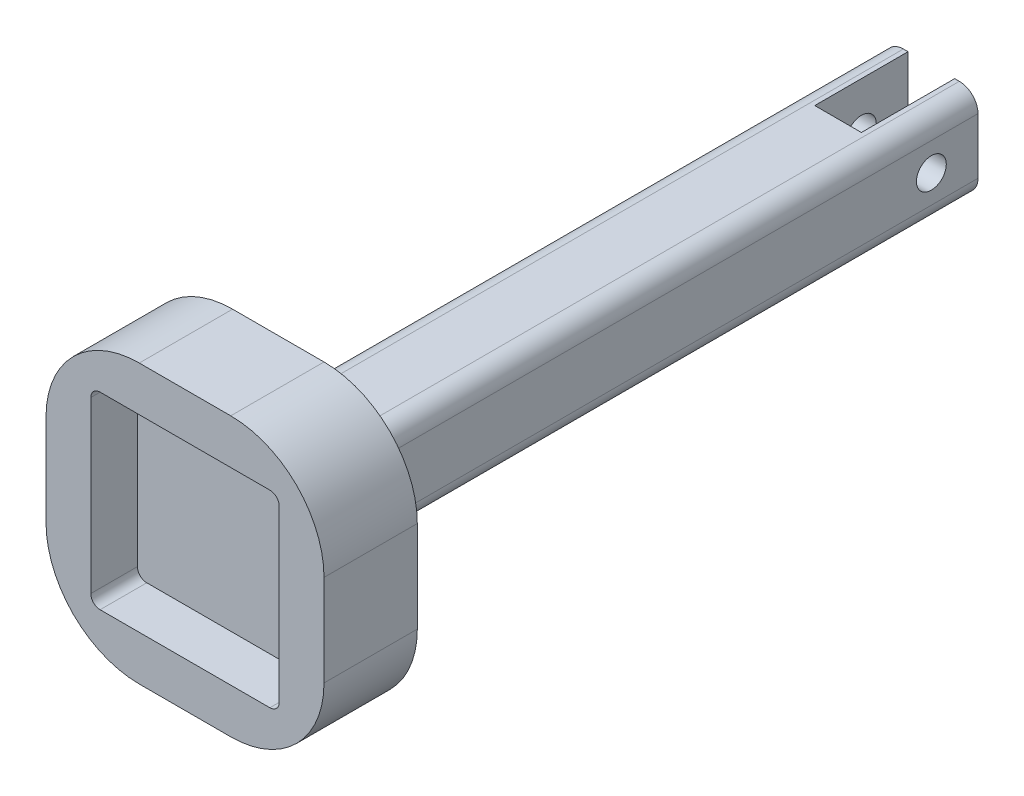
SolidWorks part; units mm, degrees
ref_plane "正面" through (0, 0, 0) normal (0, 0, 1) x (1, 0, 0)
ref_plane "平面" through (0, 0, 0) normal (0, 1, 0) x (1, 0, 0)
ref_plane "右側面" through (0, 0, 0) normal (1, 0, 0) x (0, 0, -1)
sketch "ｽｹｯﾁ1" plane through (0, 0, 0) normal (0, 0, 1) x (1, 0, 0)
  line L1 (-14.9, -14.9) -> (14.9, -14.9)
  line L2 (-14.9, -14.9) -> (-14.9, 14.9)
  line L3 (-14.9, 14.9) -> (14.9, 14.9)
  line L4 (14.9, -14.9) -> (14.9, 14.9)
  line L5 (-14.9, -14.9) -> (14.9, 14.9) construction
  line L6 (-14.9, 14.9) -> (14.9, -14.9) construction
  point P0 (0, 0)
  dimension "D1" = 29.8
  dimension "D2" = 29.8
extrude "ﾎﾞｽ - 押し出し1" add sketch "ｽｹｯﾁ1" along normal blind 10 contours L3 L4 L1 L2
fillet "ﾌｨﾚｯﾄ1" radius 10 4 edges at (14.9, -14.9, 5) (-14.9, -14.9, 5) (14.9, 14.9, 5) (-14.9, 14.9, 5)
sketch "ｽｹｯﾁ2" plane through (0, 0, 0) normal (0, 0, -1) x (-1, 0, 0)
  line L1 (-5, -5) -> (5, -5)
  line L2 (-5, -5) -> (-5, 5)
  line L3 (-5, 5) -> (5, 5)
  line L4 (5, -5) -> (5, 5)
  line L5 (-5, -5) -> (5, 5) construction
  line L6 (-5, 5) -> (5, -5) construction
  point P0 (0, 0)
  dimension "D1" = 10
  dimension "D2" = 10
extrude "ﾎﾞｽ - 押し出し2" add sketch "ｽｹｯﾁ2" along normal blind 70
sketch "ｽｹｯﾁ3" plane through (0, 5, 0) normal (0, 1, 0) x (1, 0, 0)
  line L0 (-5, 70) -> (5, 70) construction
  line L1 (2.5, 70) -> (-2.5, 70)
  line L2 (2.5, 70) -> (2.5, 60)
  line L3 (2.5, 60) -> (-2.5, 60)
  line L4 (-2.5, 70) -> (-2.5, 60)
  point P6 (0, 70)
  point P7 (0, 70)
  dimension "D1" = 5
  dimension "D2" = 10
extrude "ｶｯﾄ - 押し出し1" cut sketch "ｽｹｯﾁ3" against normal through all
sketch "ｽｹｯﾁ4" plane through (5, 0, 0) normal (1, 0, 0) x (0, 0, -1)
  line L0 (70, 5) -> (70, -5) construction
  circle A0 centre (65, 0) radius 1.6
  dimension "D1" = 3.2
  dimension "D2" = 5
extrude "ｶｯﾄ - 押し出し2" cut sketch "ｽｹｯﾁ4" against normal through all
sketch "ｽｹｯﾁ5" plane through (0, 0, 10) normal (0, 0, 1) x (1, 0, 0)
  line L1 (-9.1, -10.1) -> (9.1, -10.1)
  line L2 (-10.1, -9.1) -> (-10.1, 9.1)
  line L3 (-9.1, 10.1) -> (9.1, 10.1)
  line L4 (10.1, -9.1) -> (10.1, 9.1)
  line L5 (-10.1, -10.1) -> (10.1, 10.1) construction
  line L6 (-10.1, 10.1) -> (10.1, -10.1) construction
  arc A0 (-9.1, -10.1) -> (-10.1, -9.1) centre (-9.1, -9.1) cw
  arc A1 (9.1, -10.1) -> (10.1, -9.1) centre (9.1, -9.1) ccw
  arc A2 (9.1, 10.1) -> (10.1, 9.1) centre (9.1, 9.1) cw
  arc A3 (-10.1, 9.1) -> (-9.1, 10.1) centre (-9.1, 9.1) cw
  point P0 (0, 0)
  dimension "D3" = 1
  dimension "D1" = 20.2
  dimension "D2" = 20.2
extrude "ｶｯﾄ - 押し出し3" cut sketch "ｽｹｯﾁ5" against normal blind 5
fillet "ﾌｨﾚｯﾄ3" radius 2 4 edges at (-5, -5, -35) (5, -5, -35) (-5, 5, -35) (5, 5, -35)
